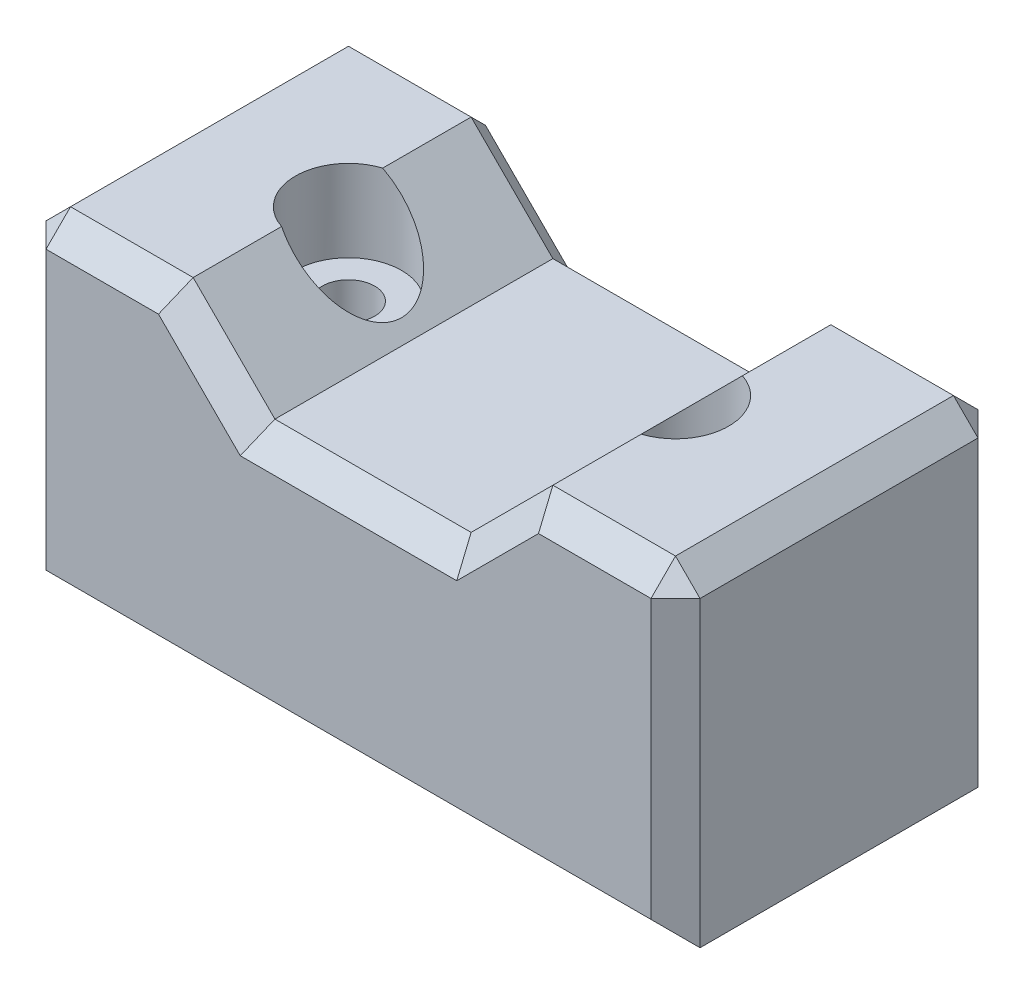
SolidWorks part; units mm, degrees
ref_plane "Front" through (0, 0, 0) normal (0, 0, 1) x (1, 0, 0)
ref_plane "Top" through (0, 0, 0) normal (0, 1, 0) x (1, 0, 0)
ref_plane "Right" through (0, 0, 0) normal (1, 0, 0) x (0, 0, -1)
sketch "草图1" plane through (0, 0, 0) normal (0, 1, 0) x (1, 0, 0)
  line L0 (0, 0) -> (10, 0) construction
  line L1 (-20, -10) -> (20, -10)
  line L2 (-20, -10) -> (-20, 10)
  line L3 (-20, 10) -> (20, 10)
  line L4 (20, -10) -> (20, 10)
  line L5 (-20, -10) -> (20, 10) construction
  line L6 (-20, 10) -> (20, -10) construction
  line L7 (0, 0) -> (0, 10) construction
  circle A0 centre (10, 0) radius 1.6
  circle A1 centre (-10, 0) radius 1.6
  point P0 (0, 0)
  dimension "D3" = 10
  dimension "D4" = 3.2
  dimension "D1" = 20
  dimension "D2" = 40
extrude "凸台-拉伸1" add sketch "草图1" along normal blind 20
sketch "草图2" plane through (0, 0, 10) normal (0, 0, 1) x (1, 0, 0)
  line L0 (0, 20) -> (0, 15) construction
  line L1 (-20, 20) -> (20, 20) construction
  line L2 (-6, 15) -> (6, 15)
  line L3 (6, 15) -> (11, 20)
  line L4 (-6, 15) -> (-11, 20)
  line L5 (-11, 20) -> (11, 20)
  dimension "D1" = 5
  dimension "D2" = 6
  dimension "D3" = 135
extrude "切除-拉伸1" cut sketch "草图2" against normal blind 20
sketch "草图3" plane through (0, 20, 0) normal (0, 1, 0) x (1, 0, 0)
  circle A0 centre (10, 0) radius 3.25
  circle A1 centre (-10, 0) radius 3.25
  dimension "D1" = 6.5
  dimension "D2" = 6.5
extrude "切除-拉伸2" cut sketch "草图3" against normal up to surface (5 mm away) up to face at (0, 15, 0)
chamfer "倒角1" distance 1.5 angle 45 18 edges at (8.5, 17.5, 10) (15.5, 20, 10) (20, 10, 10) (0, 0, 10) (-20, 10, 10) (0, 15, 10) (-8.5, 17.5, 10) (-15.5, 20, 10) (-20, 10, -10) (0, 0, -10) (20, 10, -10) (20, 20, 0) (15.5, 20, -10) (8.5, 17.5, -10) (0, 15, -10) (-8.5, 17.5, -10) (-15.5, 20, -10) (-20, 20, 0)
